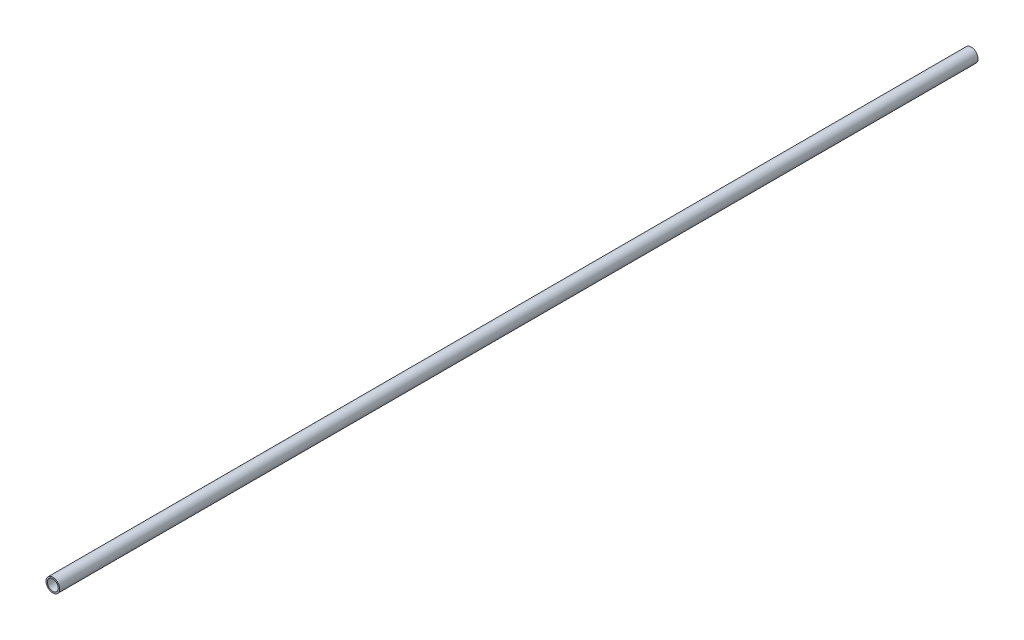
SolidWorks part; units mm, degrees
material "ST37.0 (W 1.0254)"
ref_plane "Front Plane" through (0, 0, 0) normal (0, 0, 1) x (1, 0, 0)
ref_plane "Top Plane" through (0, 0, 0) normal (0, 1, 0) x (1, 0, 0)
ref_plane "Right Plane" through (0, 0, 0) normal (1, 0, 0) x (0, 0, -1)
sketch "Sketch1" plane through (0, 0, 0) normal (0, 0, 1) x (1, 0, 0)
  line L0 (0, 0) -> (0, 25.8326) construction
  line L1 (0, 0) -> (20.8541, 0) construction
  circle A0 centre (0, 0) radius 4
  circle A1 centre (0, 0) radius 5
extrude "Extrude1" add sketch "Sketch1" along normal blind 673
